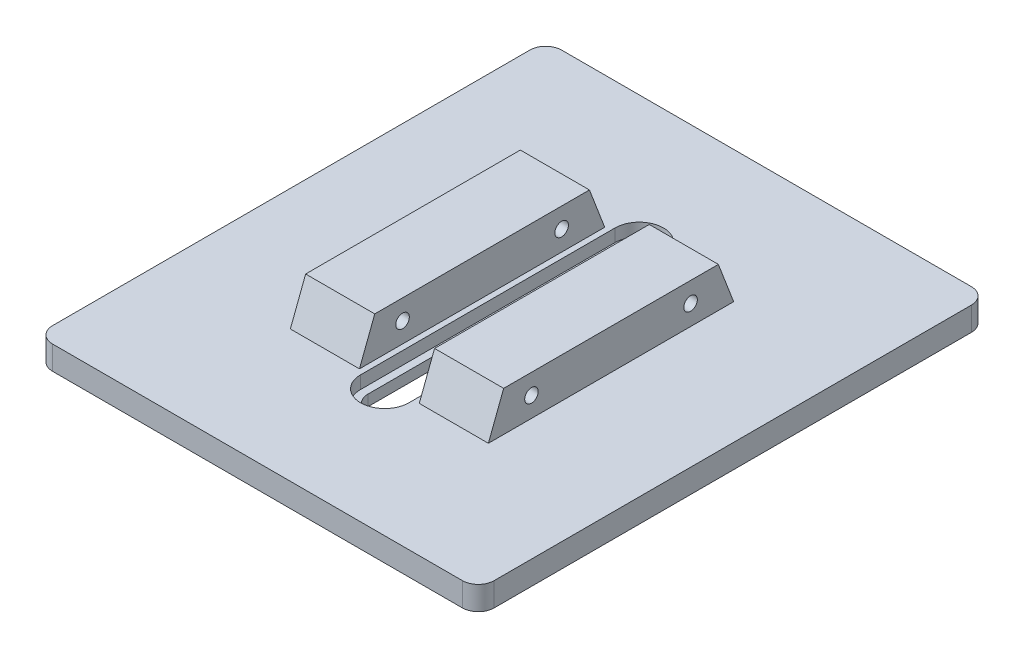
SolidWorks part; units mm, degrees
ref_plane "Front Plane" through (0, 0, 0) normal (0, 0, 1) x (1, 0, 0)
ref_plane "Top Plane" through (0, 0, 0) normal (0, 1, 0) x (1, 0, 0)
ref_plane "Right Plane" through (0, 0, 0) normal (1, 0, 0) x (0, 0, -1)
sketch "Sketch1" plane through (0, 0, 0) normal (0, 1, 0) x (1, 0, 0)
  line L1 (-59.4931, 81.4017) -> (28.6449, 81.4017)
  line L2 (-59.4931, 81.4017) -> (-59.4931, -20.1983)
  line L3 (-59.4931, -20.1983) -> (28.6449, -20.1983)
  line L4 (28.6449, 81.4017) -> (28.6449, -20.1983)
  dimension "D1" = 88.138
  dimension "D2" = 101.6
  dimension "D3" = 28.6449
  dimension "D4" = 81.4017
extrude "Boss-Extrude1" add sketch "Sketch1" along normal blind 12.7
sketch "Sketch2" plane through (0, 12.7, 0) normal (0, 1, 0) x (1, 0, 0)
  line L0 (-59.4931, -20.1983) -> (28.6449, -20.1983) construction
  line L1 (-59.4931, 81.4017) -> (-35.1853, 81.4017)
  line L2 (-59.4931, 81.4017) -> (-59.4931, -20.1983)
  line L3 (-59.4931, -20.1983) -> (-35.1853, -20.1983)
  line L4 (-35.1853, 81.4017) -> (-35.1853, -20.1983)
  line L5 (-15.4241, 81.4017) -> (-15.4241, -20.1983) construction
  line L6 (28.6449, 81.4017) -> (4.3371, 81.4017)
  line L7 (28.6449, 81.4017) -> (28.6449, -20.1983)
  line L8 (28.6449, -20.1983) -> (4.3371, -20.1983)
  line L9 (4.3371, 81.4017) -> (4.3371, -20.1983)
  line L10 (28.6449, 81.4017) -> (-59.4931, 81.4017) construction
  line L12 (-21.3931, -20.1983) -> (-9.4551, -20.1983)
  line L13 (-21.3931, -20.1983) -> (-21.3931, 81.4017)
  line L14 (-21.3931, 81.4017) -> (-9.4551, 81.4017)
  line L15 (-9.4551, -20.1983) -> (-9.4551, 81.4017)
  line L16 (-21.3931, -20.1983) -> (-9.4551, 81.4017) construction
  line L17 (-21.3931, 81.4017) -> (-9.4551, -20.1983) construction
  point P16 (-15.4241, 30.6017)
  dimension "D1" = 24.3078
  dimension "D2" = 24.3078
  dimension "D3" = 11.938
extrude "Cut-Extrude1" cut sketch "Sketch2" against normal blind 7.9756
sketch "Sketch3" plane through (0, 4.7244, 0) normal (0, 1, 0) x (1, 0, 0)
  line L0 (-15.4241, 81.4017) -> (-15.4241, -20.1983) construction
  line L1 (-9.4551, 81.4017) -> (-21.3931, 81.4017) construction
  line L2 (-21.3931, -20.1983) -> (-9.4551, -20.1983) construction
  line L3 (-15.4241, 5.2017) -> (-15.4241, 56.0017) construction
  line L4 (-18.7261, 5.2017) -> (-18.7261, 56.0017)
  line L5 (-12.1221, 5.2017) -> (-12.1221, 56.0017)
  arc A0 (-18.7261, 5.2017) -> (-12.1221, 5.2017) centre (-15.4241, 5.2017) ccw
  arc A1 (-12.1221, 56.0017) -> (-18.7261, 56.0017) centre (-15.4241, 56.0017) ccw
  point P8 (-15.4241, 30.6017)
  dimension "D2" = 3.302
  dimension "D1" = 50.8
extrude "Cut-Extrude2" cut sketch "Sketch3" against normal through all
sketch "Sketch4" plane through (0, 4.7244, 0) normal (0, 1, 0) x (1, 0, 0)
  line L0 (-15.4241, 81.4017) -> (-15.4241, -20.1983) construction
  line L1 (-9.4551, 81.4017) -> (-21.3931, 81.4017) construction
  line L2 (-21.3931, -20.1983) -> (-9.4551, -20.1983) construction
  line L3 (-15.4241, 5.2017) -> (-15.4241, 56.0017) construction
  line L4 (-20.2501, 5.2017) -> (-20.2501, 56.0017)
  line L5 (-10.5981, 5.2017) -> (-10.5981, 56.0017)
  arc A0 (-20.2501, 5.2017) -> (-10.5981, 5.2017) centre (-15.4241, 5.2017) ccw
  arc A1 (-10.5981, 56.0017) -> (-20.2501, 56.0017) centre (-15.4241, 56.0017) ccw
  point P8 (-15.4241, 30.6017)
  dimension "D2" = 4.826
  dimension "D1" = 50.8
extrude "Cut-Extrude3" cut sketch "Sketch4" against normal blind 2.54
hole_wizard "#6-32 Tapped Hole1" positions "Sketch5" profile "Sketch7" tap size "#6-32" standard "ANSI Inch" end condition through all
sketch "Sketch5" plane through (4.3371, 0, 0) normal (1, 0, 0) x (0, 0, -1)
  line L4 (81.4017, 12.7) -> (-20.1983, 12.7) construction
  line L5 (30.6017, 12.7) -> (30.6017, 4.7244) construction
  line L6 (-20.1983, 4.7244) -> (81.4017, 4.7244) construction
  line L7 (81.4017, 8.7122) -> (-20.1983, 8.7122) construction
  line L8 (81.4017, 4.7244) -> (81.4017, 12.7) construction
  line L9 (-20.1983, 4.7244) -> (-20.1983, 12.7) construction
  point P17 (46.4767, 8.7122)
  point P19 (14.7267, 8.7122)
  dimension "D2" = 15.875
  dimension "D3" = 15.875
sketch "Sketch7" plane through (4.3371, 8.7122, -14.7267) normal (0, 1, 0) x (0, 0, -1)
  line L0 (0, 0) -> (0, 63.8302)
  line L1 (0, 63.8302) -> (1.3525, 63.8302)
  line L2 (1.3525, 63.8302) -> (1.3525, 0)
  line L5 (1.3525, 0) -> (0, 0)
  line L11 (0, -6.35) -> (0, 107.95) construction
  dimension "Thread Major Dia." = 2.7051
  dimension "Thru Tap Drill Depth" = 63.8302
fillet "Fillet1" radius 3.175 4 edges at (-59.4931, 2.3622, 20.1983) (28.6449, 2.3622, 20.1983) (28.6449, 2.3622, -81.4017) (-59.4931, 2.3622, -81.4017)
sketch "Sketch8" plane through (-35.1853, 0, 0) normal (-1, 0, 0) x (0, 0, 1)
  line L0 (-6.1288, 4.7244) -> (-9.2068, 12.7762)
  line L1 (-78.2267, 4.7244) -> (17.0233, 4.7244) construction
  line L2 (-6.7877, 6.4479) -> (-9.2068, 12.7762) construction
  line L3 (-55.0746, 4.7244) -> (-51.9966, 12.7762)
  line L5 (-51.9966, 12.7762) -> (-54.4158, 6.4479) construction
  line L6 (-55.0746, 4.7244) -> (-81.4017, 4.7244)
  line L7 (-81.4017, 4.7244) -> (-81.4017, 12.7)
  line L8 (-51.9966, 12.7762) -> (-44.1253, 33.3671) construction
  line L9 (-51.9966, 12.7762) -> (-81.4017, 12.7)
  line L10 (-6.1288, 4.7244) -> (20.1983, 4.7244)
  line L11 (20.1983, 4.7244) -> (20.1983, 12.7)
  line L12 (20.1983, 12.7) -> (-9.2068, 12.7762)
extrude "Cut-Extrude4" cut sketch "Sketch8" against normal through all
